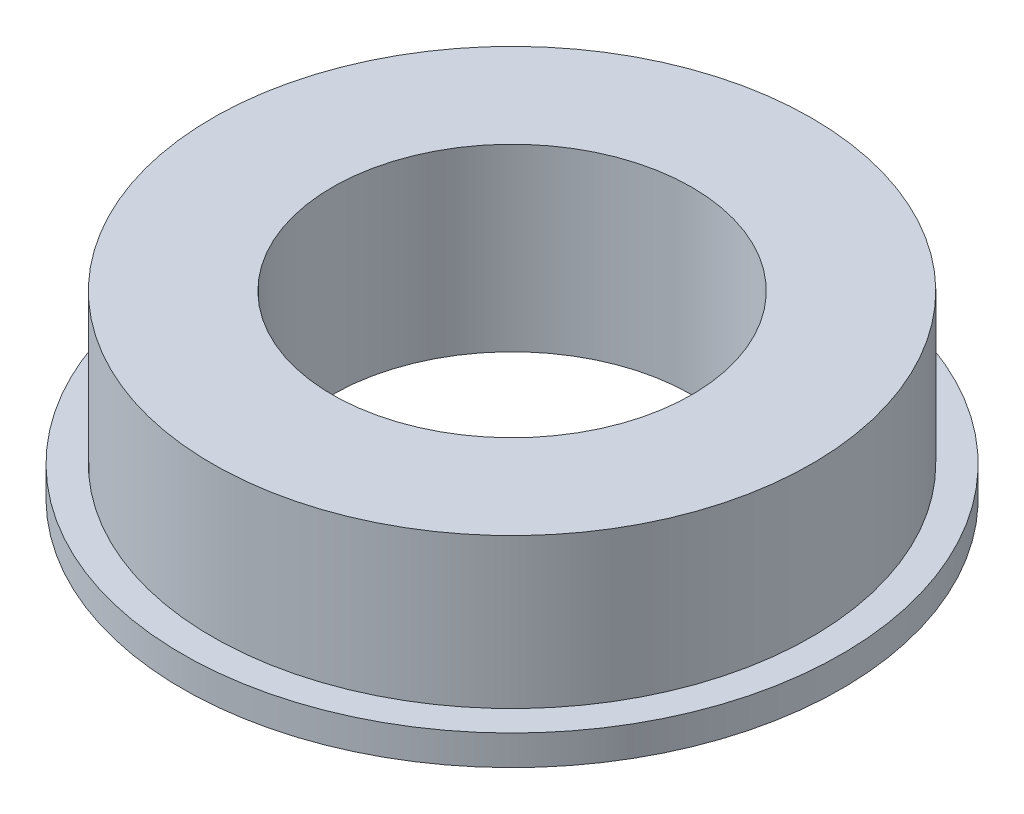
SolidWorks part; units mm, degrees
material "延性铁"
ref_plane "前视基准面" through (0, 0, 0) normal (0, 0, 1) x (1, 0, 0)
ref_plane "上视基准面" through (0, 0, 0) normal (0, 1, 0) x (1, 0, 0)
ref_plane "右视基准面" through (0, 0, 0) normal (1, 0, 0) x (0, 0, -1)
sketch "草图1" plane through (0, 0, 0) normal (0, 0, 1) x (1, 0, 0)
  line L0 (0, 0) -> (0, 6.8067)
  line L2 (3, 3) -> (5, 3)
  line L3 (3, 3) -> (3, 0)
  line L4 (3, 0) -> (5, 0)
  line L5 (5, 3) -> (5, 0)
  line L6 (5, 0) -> (5.5, 0)
  line L7 (5, 0) -> (5, 0.5)
  line L8 (5, 0.5) -> (5.5, 0.5)
  line L9 (5.5, 0) -> (5.5, 0.5)
  dimension "D1" = 5
  dimension "D2" = 2
  dimension "D3" = 3
  dimension "D4" = 0.5
  dimension "D5" = 2.5
revolve "旋转1" add sketch "草图1" angle 360 about L0
